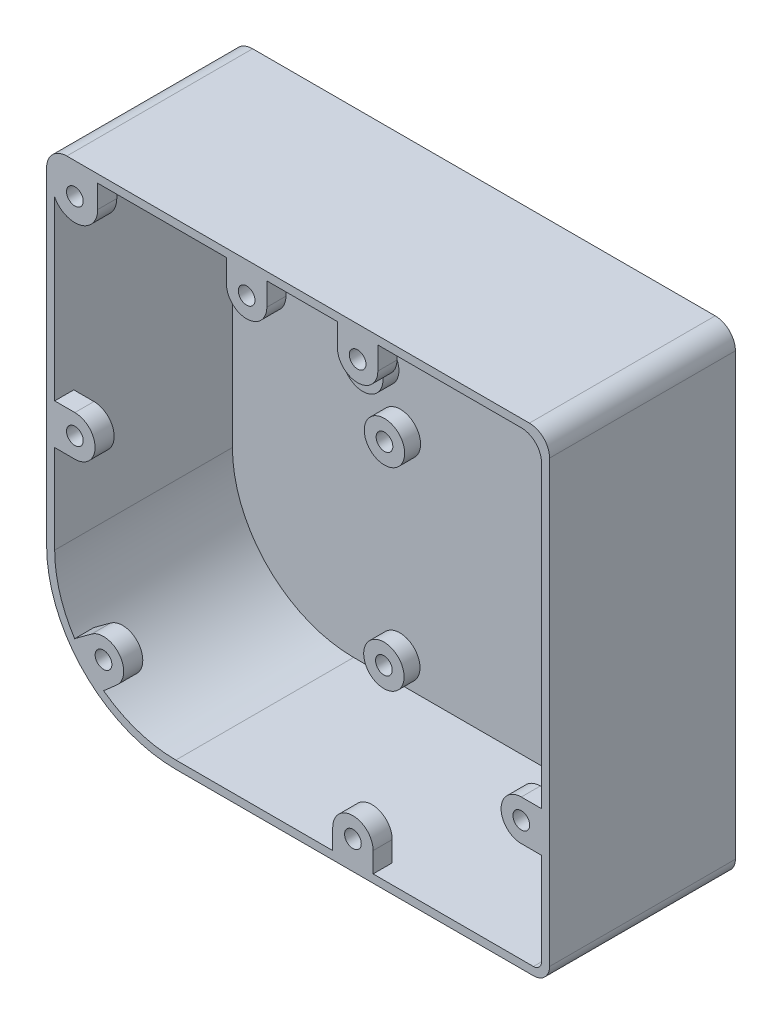
SolidWorks part; units mm, degrees
material "Custom Plastic"
ref_plane "X-Y Datum" through (0, 0, 0) normal (0, 0, 1) x (1, 0, 0)
ref_plane "X-Z Datum" through (0, 0, 0) normal (0, 1, 0) x (1, 0, 0)
ref_plane "Y-Z Datum" through (0, 0, 0) normal (1, 0, 0) x (0, 0, -1)
sketch "Sketch1" plane through (0, 0, 0) normal (0, 0, 1) x (1, 0, 0)
  line L0 (1.8162, 48.1563) -> (125.4513, 48.1563) construction
  line L1 (24.3593, 48.1563) -> (24.3593, 120.2923) construction
  line L3 (24.3593, 120.2923) -> (125.4513, 120.2923) construction
  line L8 (125.4513, 48.1563) -> (125.4513, 120.2923) construction
  line L33 (24.3593, 120.2923) -> (1.8162, 120.2923) construction
  line L34 (24.3593, 120.2923) -> (24.3593, 48.1563) construction
  line L35 (63.6337, 48.1563) -> (63.6337, 43.0763) construction
  line L36 (1.8162, 120.2923) -> (1.8162, 48.1563) construction
  line L37 (8.9602, -19.4077) -> (8.9602, 43.0763) construction
  line L38 (8.9602, -19.4077) -> (118.3072, -19.4077) construction
  line L39 (118.3072, -19.4077) -> (118.3072, 43.0763) construction
  line L40 (118.3072, 43.0763) -> (8.9602, 43.0763) construction
  line L41 (1.8162, 120.2923) -> (1.8162, 122.8323) construction
  line L42 (1.8162, 120.2923) -> (0.5462, 120.2923) construction
  line L43 (1.8162, 48.1563) -> (0.5462, 48.1563) construction
  line L44 (8.9602, -19.4077) -> (8.9602, -21.9477) construction
  line L45 (125.4513, 120.2923) -> (127.9913, 120.2923) construction
  line L47 (0.5462, 122.8323) -> (127.9913, 122.8323)
  line L48 (0.5462, 122.8323) -> (0.5462, -21.9477)
  line L49 (0.5462, -21.9477) -> (127.9913, -21.9477)
  line L50 (127.9913, 122.8323) -> (127.9913, -21.9477)
  circle A17 centre (30.4553, 114.1963) radius 2.1 construction
  circle A18 centre (119.8633, 115.2123) radius 2.1 construction
  circle A19 centre (119.6813, 54.2533) radius 2.1 construction
  circle A20 centre (29.4393, 53.2363) radius 2.1 construction
  circle A21 centre (13.7862, -13.9467) radius 2.1 construction
  circle A22 centre (13.7862, -13.9467) radius 2.1 construction
  circle A23 centre (13.7672, 38.1213) radius 2.1 construction
  circle A24 centre (113.4812, -13.9467) radius 2.1 construction
  circle A25 centre (113.4812, 37.9963) radius 2.1 construction
  point P39 (0, 0)
sketch "Sketch2" plane through (0, 0, 0) normal (0, 0, 1) x (1, 0, 0)
  line L4 (127.9913, 122.8323) -> (127.9913, 50.0171)
  line L6 (56.0834, 120.2923) -> (56.0834, 122.8323)
  line L7 (-15.891, 122.8323) -> (-15.891, 50.0171)
  line L8 (127.9913, 50.0171) -> (-15.891, 50.0171)
  line L9 (115.3693, 122.8323) -> (-15.891, 50.0171) construction
  line L10 (-3.269, 122.8323) -> (127.9913, 50.0171) construction
  line L11 (56.0834, 122.8323) -> (-15.891, 122.8323)
  line L12 (56.0834, 122.8323) -> (127.9913, 122.8323)
  circle A7 centre (11.609, 89.9257) radius 27.5
  circle A8 centre (100.509, 89.979) radius 27.5
  circle A9 centre (56.0501, 79.7923) radius 6.477
  circle A10 centre (56.0679, 100.1123) radius 6.477
  circle A11 centre (36.9798, 56.4941) radius 6.477
  circle A12 centre (56.0346, 62.0123) radius 2.4
  circle A13 centre (56.0834, 117.8923) radius 2.4
  point P14 (56.0501, 89.9257)
sketch "Sketch5" plane through (0, 0, 0) normal (0, 0, 1) x (1, 0, 0)
  line L0 (11.609, 89.9257) -> (-7.8365, 109.3711) construction
  line L5 (-7.8365, 109.3711) -> (-14.1227, 115.6573) construction
  line L6 (100.509, 89.979) -> (119.9545, 109.4244) construction
  line L7 (119.9545, 109.4244) -> (126.2407, 115.7106) construction
  line L8 (100.509, 89.979) -> (81.0636, 109.4244) construction
  line L9 (81.0636, 109.4244) -> (74.7774, 115.7106) construction
  line L10 (11.609, 89.9257) -> (31.0544, 109.3711) construction
  line L11 (31.0544, 109.3711) -> (37.3406, 115.6573) construction
  line L12 (-20.4727, 50.4423) -> (140.3848, 50.4423) construction
  line L13 (-20.4727, 122.8323) -> (132.5907, 122.8323)
  line L14 (-20.4727, 122.8323) -> (-20.4727, -21.9477)
  line L15 (-20.4727, -21.9477) -> (132.5907, -21.9477)
  line L16 (132.5907, 122.8323) -> (132.5907, -21.9477)
  circle A0 centre (126.2407, -14.826) radius 6.35 construction
  circle A2 centre (-14.1227, -14.7726) radius 6.35 construction
  circle A4 centre (11.609, 89.9257) radius 27.5 construction
  circle A5 centre (-14.1227, 115.6573) radius 6.35 construction
  circle A6 centre (100.509, 89.979) radius 27.5 construction
  circle A7 centre (126.2407, 115.7106) radius 6.35 construction
  circle A8 centre (74.7774, 115.7106) radius 6.35 construction
  circle A9 centre (37.3406, 115.6573) radius 6.35 construction
  circle A11 centre (126.2407, 50.4423) radius 6.35 construction
  circle A12 centre (-14.1227, 50.4423) radius 6.35 construction
extrude "Boss-Extrude4" add sketch "Sketch5" along normal blind 55.88
fillet "Fillet1" radius 38.1 1 edges at (-20.4727, -21.9477, 27.94)
fillet "Fillet2" radius 2.54 1 edges at (132.5907, -21.9477, 27.94)
shell "Shell3" thickness 2.54
sketch "Sketch7" plane through (0, 0, 0) normal (0, 0, 1) x (1, 0, 0)
  line L0 (131.9557, -7.6387) -> (131.9557, -19.4077) construction
  line L1 (127.9125, 52.7283) -> (26.8205, 52.7283) construction
  line L2 (127.9125, 52.7283) -> (127.9125, -19.4077) construction
  line L3 (127.9125, -19.4077) -> (26.8205, -19.4077) construction
  line L4 (26.8205, 52.7283) -> (26.8205, -19.4077) construction
  line L5 (127.9125, -19.4077) -> (150.4557, -19.4077) construction
  line L6 (127.9125, -19.4077) -> (127.9125, 52.7283) construction
  line L7 (127.9125, 52.7283) -> (150.4557, 52.7283) construction
  line L8 (150.4557, -19.4077) -> (150.4557, 52.7283) construction
  line L9 (20.7037, 57.8083) -> (20.7037, 120.2923) construction
  line L10 (20.7037, 57.8083) -> (130.0507, 57.8083) construction
  line L11 (131.9557, -7.6387) -> (131.9557, 52.7283) construction
  line L12 (130.0507, 57.8083) -> (130.0507, 120.2923) construction
  line L13 (130.0507, 120.2923) -> (20.7037, 120.2923) construction
  line L14 (132.5907, -19.4077) -> (131.9557, -19.4077) construction
  line L15 (132.5907, 122.8323) -> (130.0507, 122.8323) construction
  line L16 (0.5462, 122.8323) -> (127.9913, 122.8323) construction
  line L17 (130.0507, 122.8323) -> (130.0507, 120.2923) construction
  circle A0 centre (121.5625, -13.3117) radius 2.1 construction
  circle A1 centre (32.1545, -14.3277) radius 2.1 construction
  circle A2 centre (32.3365, 46.6313) radius 2.1 construction
  circle A3 centre (122.5785, 47.6483) radius 2.1 construction
  circle A4 centre (122.5785, 47.6483) radius 6.35
  circle A5 centre (121.5625, -13.3117) radius 6.35
  circle A6 centre (32.3365, 46.6313) radius 6.35
  circle A7 centre (32.1545, -14.3277) radius 6.35
  circle A8 centre (25.5297, 63.2693) radius 2.1 construction
  circle A9 centre (25.5297, 63.2693) radius 2.1 construction
  circle A10 centre (25.5107, 115.3373) radius 2.1 construction
  circle A11 centre (125.2247, 63.2693) radius 2.1 construction
  circle A12 centre (125.2247, 115.2123) radius 2.1 construction
  circle A13 centre (125.2247, 115.2123) radius 6.35
  circle A14 centre (125.2247, 63.2693) radius 6.35
  circle A15 centre (25.5107, 115.3373) radius 6.35
  circle A16 centre (25.5297, 63.2693) radius 6.35
extrude "Boss-Extrude5" add sketch "Sketch7" along normal blind 5
sketch "Sketch8" plane through (0, 0, 5) normal (0, 0, 1) x (1, 0, 0)
  circle A0 centre (25.5107, 115.3373) radius 2.625
  circle A1 centre (25.5297, 63.2693) radius 2.625
  circle A2 centre (32.3365, 46.6313) radius 2.625
  circle A3 centre (32.1545, -14.3277) radius 2.625
  circle A4 centre (125.2247, 63.2693) radius 2.625
  circle A5 centre (125.2247, 115.2123) radius 2.625
  circle A6 centre (122.5785, 47.6483) radius 2.625
  circle A7 centre (121.5625, -13.3117) radius 2.625
extrude "Cut-Extrude1" cut sketch "Sketch8" against normal blind 5
sketch "Sketch9" plane through (0, 0, 55.88) normal (0, 0, 1) x (1, 0, 0)
  line L0 (-6.9476, 115.6573) -> (-6.9476, 122.8323)
  line L1 (-20.4727, 122.8323) -> (132.5907, 122.8323) construction
  line L2 (-6.9476, 122.8323) -> (-20.4727, 122.8323)
  line L3 (-20.4727, 115.6573) -> (-20.4727, 122.8323)
  line L4 (-20.4727, 122.8323) -> (-20.4727, -21.9477) construction
  line L5 (-20.4727, 115.6573) -> (-20.4727, 112.3168)
  line L6 (33.5306, 115.6573) -> (33.5306, 122.8323)
  line L7 (33.5306, 122.8323) -> (46.2306, 122.8323)
  line L8 (46.2306, 122.8323) -> (46.2306, 115.6573)
  line L9 (68.4274, 115.7106) -> (68.4274, 122.8323)
  line L10 (68.4274, 122.8323) -> (81.1274, 122.8323)
  line L11 (81.1274, 122.8323) -> (81.1274, 115.7106)
  line L16 (132.5907, 122.8323) -> (132.5907, -21.9477) construction
  line L19 (126.2407, 22.2968) -> (132.5907, 22.2968)
  line L20 (126.2407, 9.5968) -> (132.5907, 9.5968)
  line L21 (132.5907, 9.5968) -> (132.5907, 22.2968)
  line L22 (-8.8805, -0.8964) -> (-14.1227, -4.7422)
  line L23 (-0.9351, -10.7884) -> (-5.0891, -14.4349)
  line L24 (-14.1227, 56.7923) -> (-20.4727, 56.7923)
  line L25 (-14.1227, 44.0923) -> (-20.4727, 44.0923)
  line L26 (-20.4727, 56.7923) -> (-20.4727, 44.0923)
  line L31 (73.2964, -21.9477) -> (73.2964, -15.5977) construction
  line L32 (-20.4727, -21.9477) -> (132.5907, -21.9477) construction
  line L33 (66.9464, -15.5977) -> (66.9464, -21.9477)
  line L34 (79.6464, -15.5977) -> (79.6464, -21.9477)
  line L35 (66.9464, -21.9477) -> (79.6464, -21.9477)
  arc A0 (-20.4727, 112.3168) -> (-6.9476, 115.6573) centre (-14.1227, 115.6573) ccw
  arc A1 (33.5306, 115.6573) -> (46.2306, 115.6573) centre (39.8806, 115.6573) ccw
  arc A2 (-14.1227, 44.0923) -> (-14.1227, 56.7923) centre (-14.1227, 50.4423) ccw
  arc A3 (68.4274, 115.7106) -> (81.1274, 115.7106) centre (74.7774, 115.7106) ccw
  arc A6 (126.2407, 22.2968) -> (126.2407, 9.5968) centre (126.2407, 15.9468) ccw
  arc A7 (-0.9351, -10.7884) -> (-8.8805, -0.8964) centre (-5.1243, -6.0163) ccw
  arc A8 (-20.4727, 16.1523) -> (17.6273, -21.9477) centre (17.6273, 16.1523) ccw construction
  circle A9 centre (-14.1227, 115.6573) radius 6.35 construction
  arc A10 (-20.4727, 16.1523) -> (17.6273, -21.9477) centre (17.6273, 16.1523) ccw construction
  arc A11 (-14.1227, -4.7422) -> (-5.0891, -14.4349) centre (-3.6836, -4.069) ccw
  arc A13 (79.6464, -15.5977) -> (66.9464, -15.5977) centre (73.2964, -15.5977) ccw
  point P20 (-9.3134, -10.7884)
extrude "Boss-Extrude6" add sketch "Sketch9" against normal blind 6
fillet "Fillet3" radius 6.35 4 edges at (-20.4727, 122.8323, 24.94) (-23.0127, 125.3723, 26.67) (132.5907, 122.8323, 27.94) (135.1307, 125.3723, 26.67)
sketch "Sketch10" plane through (0, 0, 55.88) normal (0, 0, 1) x (1, 0, 0)
  circle A0 centre (-14.1227, 115.6573) radius 2.625
  circle A1 centre (39.8806, 115.6573) radius 2.625
  circle A2 centre (74.7774, 115.7106) radius 2.625
  circle A3 centre (-14.1227, 50.4423) radius 2.625
  circle A4 centre (-5.1243, -6.0163) radius 2.625
  circle A5 centre (73.2964, -15.5977) radius 2.625
  circle A6 centre (126.2407, 15.9468) radius 2.625
extrude "Cut-Extrude2" cut sketch "Sketch10" against normal up to surface (55.88 mm away) up to face at (31.8797, 63.2693, 0)
sketch "Sketch11" plane through (0, 0, 55.88) normal (0, 0, 1) x (1, 0, 0)
  line L0 (-16.6627, 125.3723) -> (128.7807, 125.3723)
  line L1 (135.1307, 119.0223) -> (135.1307, -19.4077)
  line L2 (130.0507, -24.4877) -> (17.6273, -24.4877)
  line L3 (-23.0127, 16.1523) -> (-23.0127, 119.0223)
  circle A0 centre (-14.1227, 115.6573) radius 2.625
  arc A1 (17.6273, -24.4877) -> (-23.0127, 16.1523) centre (17.6273, 16.1523) cw
  arc A2 (128.7807, 125.3723) -> (135.1307, 119.0223) centre (128.7807, 119.0223) cw
  arc A3 (-16.6627, 125.3723) -> (-23.0127, 119.0223) centre (-16.6627, 119.0223) ccw
  arc A4 (135.1307, -19.4077) -> (130.0507, -24.4877) centre (130.0507, -19.4077) cw
  circle A5 centre (100.509, 89.979) radius 27.5 construction
  circle A6 centre (56.0501, 79.7923) radius 6.477
  circle A7 centre (56.0346, 62.0123) radius 2.4
  circle A8 centre (56.0679, 100.1123) radius 6.477
  circle A9 centre (56.0834, 117.8923) radius 2.4
  circle A10 centre (11.609, 89.9257) radius 27.5 construction
  circle A11 centre (36.9798, 56.4941) radius 6.477
  circle A13 centre (39.8806, 115.6573) radius 2.625
  circle A14 centre (74.7774, 115.7106) radius 2.625
  circle A16 centre (-14.1227, 50.4423) radius 2.625
  circle A17 centre (-5.1243, -6.0163) radius 2.625
  circle A18 centre (73.2964, -15.5977) radius 2.625
  circle A19 centre (126.2407, 15.9468) radius 2.625
  dimension "D1" = 40.64
  dimension "D2" = 6.35
  dimension "D3" = 5.08
